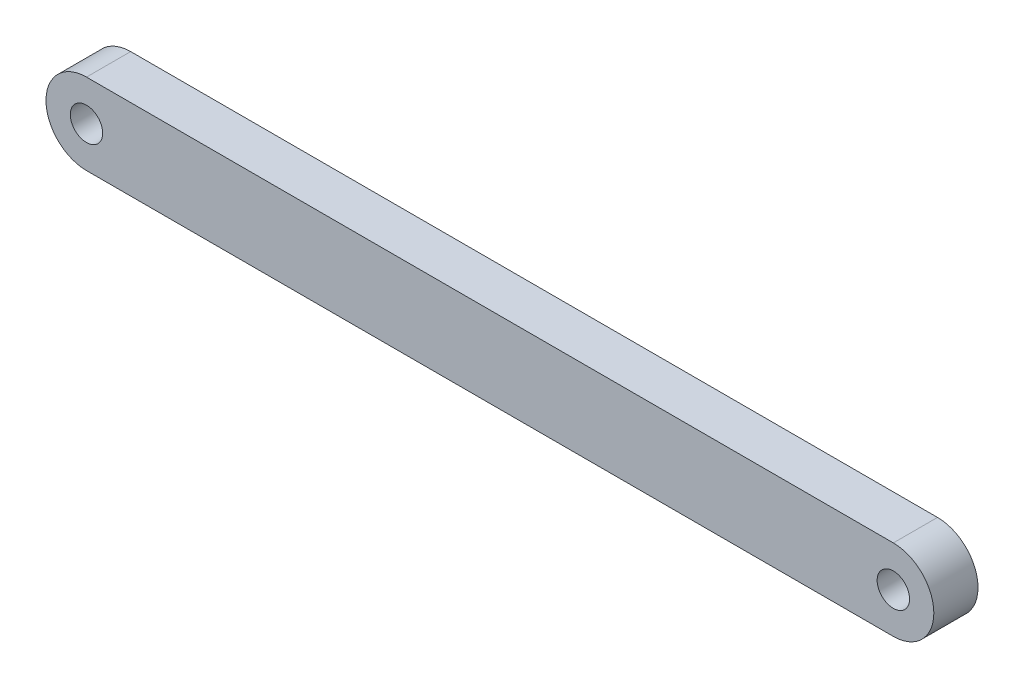
SolidWorks part; units mm, degrees
ref_plane "Front Plane" through (0, 0, 0) normal (0, 0, 1) x (1, 0, 0)
ref_plane "Top Plane" through (0, 0, 0) normal (0, 1, 0) x (1, 0, 0)
ref_plane "Right Plane" through (0, 0, 0) normal (1, 0, 0) x (0, 0, -1)
sketch "Sketch1" plane through (0, 0, 0) normal (0, 0, 1) x (1, 0, 0)
  line L0 (-10.9893, 0) -> (43.8107, 0) construction
  line L1 (-10.9893, 2.75) -> (43.8107, 2.75)
  line L2 (-10.9893, -2.75) -> (43.8107, -2.75)
  arc A0 (-10.9893, 2.75) -> (-10.9893, -2.75) centre (-10.9893, 0) ccw
  arc A1 (43.8107, -2.75) -> (43.8107, 2.75) centre (43.8107, 0) ccw
  point P3 (16.4107, 0)
  dimension "D1" = 54.8
  dimension "D2" = 5.5
extrude "Boss-Extrude1" add sketch "Sketch1" along normal blind 3
sketch "Sketch2" plane through (0, 0, 0) normal (0, 0, -1) x (-1, 0, 0)
  circle A0 centre (10.9893, 0) radius 1.1
  circle A1 centre (-43.8107, 0) radius 1.1
  dimension "D1" = 2.2
  dimension "D2" = 2.2
extrude "Cut-Extrude1" cut sketch "Sketch2" against normal blind 3
